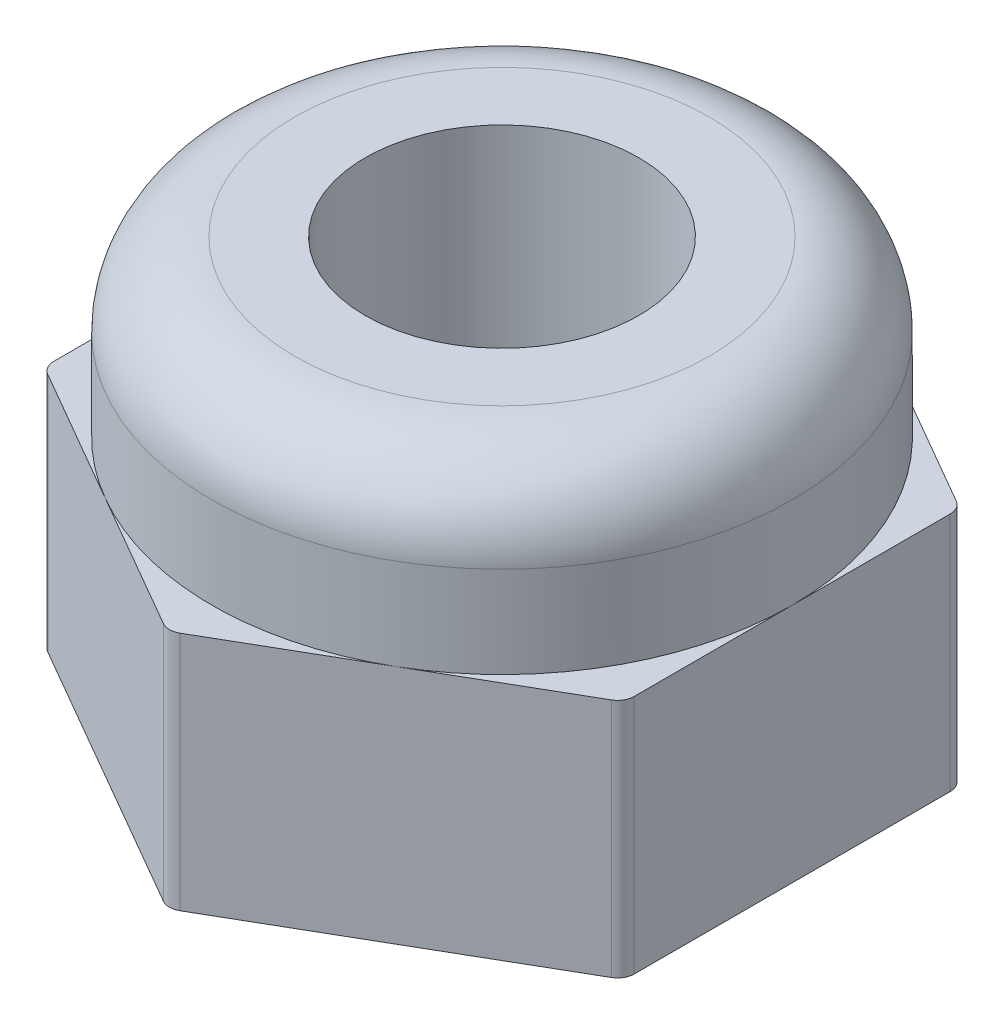
SolidWorks part; units mm, degrees
ref_plane "前视基准面" through (0, 0, 0) normal (0, 0, 1) x (1, 0, 0)
ref_plane "上视基准面" through (0, 0, 0) normal (0, 1, 0) x (1, 0, 0)
ref_plane "右视基准面" through (0, 0, 0) normal (1, 0, 0) x (0, 0, -1)
sketch "草图1" plane through (0, 0, 0) normal (0, 1, 0) x (1, 0, 0)
  line L1 (3.5, 2.0207) -> (0, 4.0415)
  line L2 (0, 4.0415) -> (-3.5, 2.0207)
  line L3 (-3.5, 2.0207) -> (-3.5, -2.0207)
  line L4 (-3.5, -2.0207) -> (0, -4.0415)
  line L5 (0, -4.0415) -> (3.5, -2.0207)
  line L6 (3.5, -2.0207) -> (3.5, 2.0207)
  circle A0 centre (0, 0) radius 3.5 construction
  dimension "D1" = 7
extrude "凸台-拉伸1" add sketch "草图1" along normal blind 2.9
sketch "草图2" plane through (0, 0, 0) normal (0, -1, 0) x (1, 0, 0)
  line L0 (3.5, 2.0207) -> (3.5, -2.0207) construction
  circle A0 centre (0, 0) radius 3.5
extrude "凸台-拉伸2" add sketch "草图2" against normal blind 5
fillet "圆角1" radius 1 1 edges at (0, 5, -3.5)
fillet "圆角2" radius 0.2 6 edges at (-3.5, 1.45, 2.0207) (-3.5, 1.45, -2.0207) (0, 1.45, -4.0415) (3.5, 1.45, -2.0207) (3.5, 1.45, 2.0207) (0, 1.45, 4.0415)
hole_wizard "M4 螺纹孔1" positions "草图3" profile "草图4" tap size "M4" standard "GB"
sketch "草图3" plane through (0, 0, 0) normal (0, -1, 0) x (-1, 0, 0)
  point P0 (0, 0)
cosmetic thread "孔螺蚊线1" parameters "D1"=8, "D2"=4
sketch "草图4" plane through (0, 0, 0) normal (1, 0, 0) x (0, 0, -1)
  line L0 (0, 0) -> (0, 11.0914)
  line L1 (0, 11.0914) -> (1.65, 10.1)
  line L2 (1.65, 10.1) -> (1.65, 0)
  line L5 (1.65, 0) -> (0, 0)
  line L10 (0, 11.0914) -> (-1.65, 10.1) construction
  line L11 (0, -6.35) -> (0, 107.95) construction
  dimension "螺纹孔钻头直径" = 3.3
  dimension "螺纹孔钻头深度" = 10.1
  dimension "导头角度" = 118
